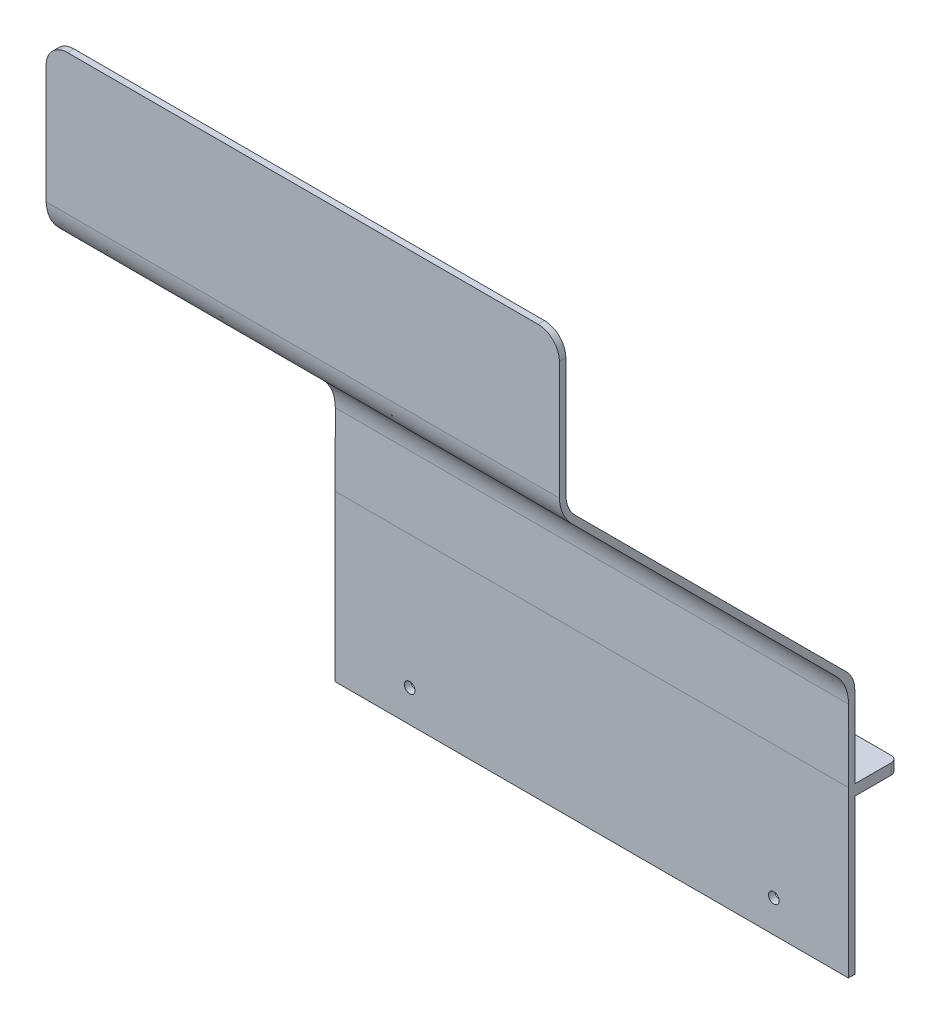
SolidWorks part; units mm, degrees
ref_plane "Front Plane" through (0, 0, 0) normal (0, 0, 1) x (1, 0, 0)
ref_plane "Top Plane" through (0, 0, 0) normal (0, 1, 0) x (1, 0, 0)
ref_plane "Right Plane" through (0, 0, 0) normal (1, 0, 0) x (0, 0, -1)
sketch "Sketch1" plane through (0, 0, 0) normal (0, 0, 1) x (1, 0, 0)
  line L1 (125, -36) -> (-125, -36)
  line L2 (125, -36) -> (125, 36)
  line L3 (125, 36) -> (-125, 36)
  line L4 (-125, -36) -> (-125, 36)
  line L5 (125, -36) -> (-125, 36) construction
  line L6 (125, 36) -> (-125, -36) construction
  point P0 (0, 0)
  dimension "D1" = 250
  dimension "D2" = 72
extrude "Boss-Extrude1" add sketch "Sketch1" along normal blind 3
sketch "Sketch2" plane through (0, 36, 0) normal (0, 1, 0) x (1, 0, 0)
  line L0 (-125, -3) -> (-125, 0) construction
  line L1 (-119.8, -3) -> (119.8, -3)
  line L2 (-119.8, -3) -> (-119.8, 20)
  line L3 (-119.8, 20) -> (119.8, 20)
  line L4 (119.8, -3) -> (119.8, 20)
  line L5 (125, -3) -> (125, 0) construction
  dimension "D1" = 5.2
  dimension "D2" = 23
  dimension "D3" = 5.2
extrude "Boss-Extrude2" add sketch "Sketch2" along normal blind 5
sketch "Sketch3" plane through (0, 41, 0) normal (0, 1, 0) x (1, 0, 0)
  line L0 (0, -55) -> (0, 55) construction
  circle A0 centre (-65, 8.5) radius 2.5
  circle A1 centre (65, 8.5) radius 2.5
  dimension "D1" = 65
extrude "Cut-Extrude1" cut sketch "Sketch3" against normal blind 5
fillet "Fillet1" radius 3 2 edges at (119.8, 38.5, -20) (-119.8, 38.5, -20)
sketch "Sketch4" plane through (0, 0, 3) normal (0, 0, 1) x (1, 0, 0)
  line L0 (-125, -36) -> (125, -36) construction
  line L1 (-125, 36) -> (-125, -36) construction
  line L2 (0, -55) -> (0, 55) construction
  circle A0 centre (-85, -21) radius 2.5
  circle A1 centre (85, -21) radius 2.5
  dimension "D1" = 15
  dimension "D2" = 40
extrude "Cut-Extrude2" cut sketch "Sketch4" against normal blind 5
sketch "Sketch6" plane through (0, 0, 3) normal (0, 0, 1) x (1, 0, 0)
  line L0 (-125, -36) -> (125, -36) construction
  line L1 (-125, 36) -> (-119.8, 36)
  line L2 (-125, 36) -> (-125, -36)
  line L3 (-125, -36) -> (-119.8, -36)
  line L4 (-119.8, 36) -> (-119.8, -36)
  line L5 (-119.8, 41) -> (-119.8, 36) construction
  line L6 (0, -12.65) -> (0, 12.65) construction
  line L7 (119.8, 36) -> (119.8, -36)
  line L8 (125, -36) -> (119.8, -36)
  line L9 (125, 36) -> (125, -36)
  line L10 (125, 36) -> (119.8, 36)
  dimension "D1" = 0
extrude "Cut-Extrude3" cut sketch "Sketch6" against normal blind 5
sketch "Sketch7" plane through (-119.8, 0, 0) normal (-1, 0, 0) x (0, 0, 1)
  line L0 (0, 41) -> (0, 74.7157)
  line L1 (-17, 41) -> (3, 41) construction
  line L2 (0, 41) -> (3, 41)
  line L3 (3, 41) -> (2.9165, 74.7157)
  line L4 (8.7744, 88.8579) -> (77.0586, 157.1421)
  line L5 (137.9165, 225.4558) -> (137.9165, 287.7744)
  line L6 (77.0586, 157.1421) -> (74.9373, 159.2635)
  line L7 (74.9373, 159.2635) -> (6.2562, 90.5824)
  line L8 (8.7744, 88.8579) -> (6.653, 90.9792)
  line L9 (6.2562, 90.5824) -> (3.8036, 88.1298)
  line L10 (0, 78.947) -> (0, 74.7157)
  line L11 (74.9373, 159.2635) -> (130.5231, 214.8492)
  line L12 (137.9165, 287.7744) -> (134.9165, 287.7744)
  line L13 (134.9165, 287.7744) -> (134.9165, 225.4558)
  line L14 (137.9165, 291.9165) -> (137.9165, 226.2843) construction
  line L15 (77.0586, 157.1421) -> (132.0586, 212.1421)
  arc A2 (130.5231, 214.8492) -> (134.9165, 225.4558) centre (119.9165, 225.4558) ccw
  arc A3 (0, 78.947) -> (3.8036, 88.1298) centre (12.9864, 78.947) cw
  arc A4 (132.0586, 212.1421) -> (137.9165, 226.2843) centre (117.9165, 226.2843) ccw construction
  spline S0 degree 2 poles (2.9165, 74.7157) (3.0324, 82.952) (8.7744, 88.8579) knots 0 0 0 1 1 1
  spline S1 degree 2 poles (132.0586, 212.1421) (137.4872, 217.7296) (137.9165, 225.4558) knots 0 0 0 1 1 1
  dimension "D1" = 15
  dimension "D2" = 12.9864
  dimension "D4" = 3
  dimension "D3" = 0
extrude "Boss-Extrude3" add sketch "Sketch7" against normal blind 239.6
sketch "Sketch8" plane through (0, 0, 137.9165) normal (0, 0, 1) x (1, 0, 0)
  line L5 (-119.8, 287.7744) -> (119.8, 287.7744)
  line L6 (-119.8, 287.7744) -> (-119.8, 290.7744)
  line L7 (-119.8, 290.7744) -> (119.8, 290.7744)
  line L8 (119.8, 287.7744) -> (119.8, 290.7744)
  dimension "D1" = 3
extrude "Boss-Extrude4" add sketch "Sketch8" against normal blind 3
fillet "Fillet3" radius 10 2 edges at (119.8, 290.7744, 136.4165) (-119.8, 290.7744, 136.4165)
sketch "Sketch10" plane through (0, 42.1631, -42.1631) normal (0, 0.7071, -0.7071) x (1, 0, 0)
  circle A0 centre (107.5, -168.3867) radius 1.8
  circle A1 centre (-107.5, -168.3867) radius 1.8
extrude "Cut-Extrude5" cut sketch "Sketch10" against normal blind 5
